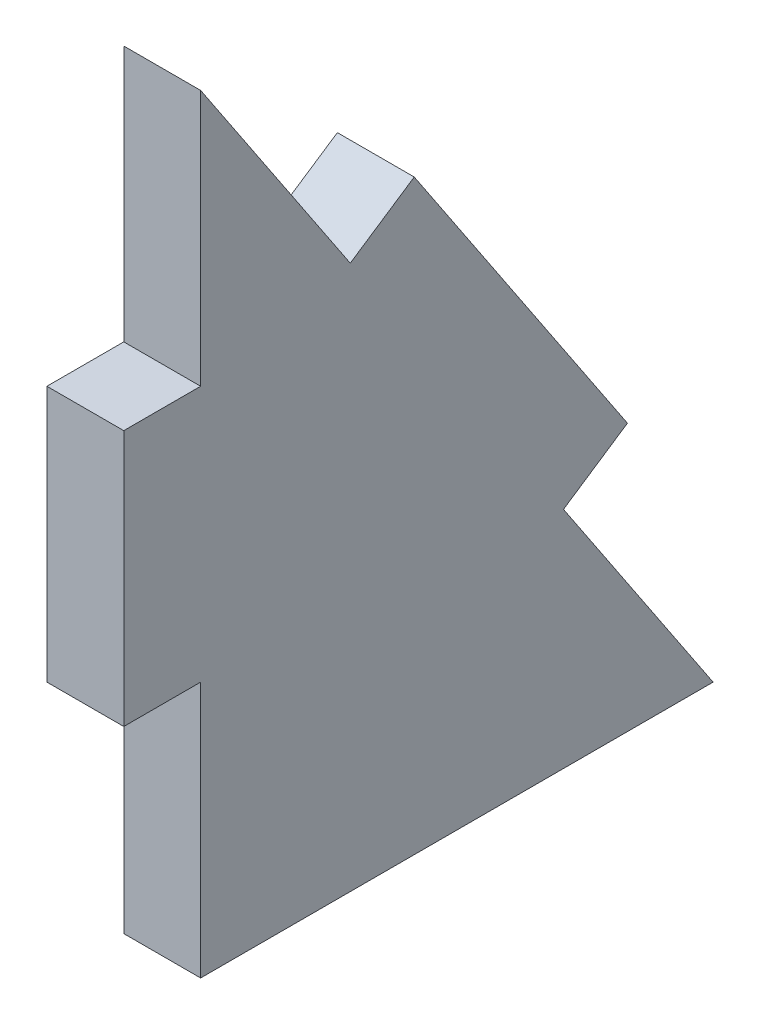
SolidWorks part; units mm, degrees
ref_plane "Front Plane" through (0, 0, 0) normal (0, 0, 1) x (1, 0, 0)
ref_plane "Top Plane" through (0, 0, 0) normal (0, 1, 0) x (1, 0, 0)
ref_plane "Right Plane" through (0, 0, 0) normal (1, 0, 0) x (0, 0, -1)
sketch "Sketch1" plane through (0, 0, 0) normal (1, 0, 0) x (0, 0, -1)
  line L0 (0, 30) -> (5.8397, 21.2404)
  line L1 (0, 0) -> (20, 0)
  line L2 (0, 0) -> (0, 10)
  line L4 (0, 20) -> (0, 30)
  line L5 (0, 20) -> (-3, 20)
  line L7 (0, 10) -> (-3, 10)
  line L8 (-3, 20) -> (-3, 10)
  line L9 (5.8397, 21.2404) -> (8.3359, 22.9045)
  line L13 (14.1603, 8.7596) -> (16.6564, 10.4237)
  line L14 (8.3359, 22.9045) -> (16.6564, 10.4237)
  line L15 (14.1603, 8.7596) -> (20, 0)
  dimension "D1" = 20
  dimension "D2" = 30
  dimension "D3" = 10
  dimension "D4" = 10
  dimension "D5" = 10.5278
  dimension "D6" = 3
  dimension "D9" = 15
  dimension "D10" = 3
  dimension "D12" = 90
  dimension "D13" = 90
  dimension "D14" = 90
extrude "Boss-Extrude1" add sketch "Sketch1" along normal blind 3
